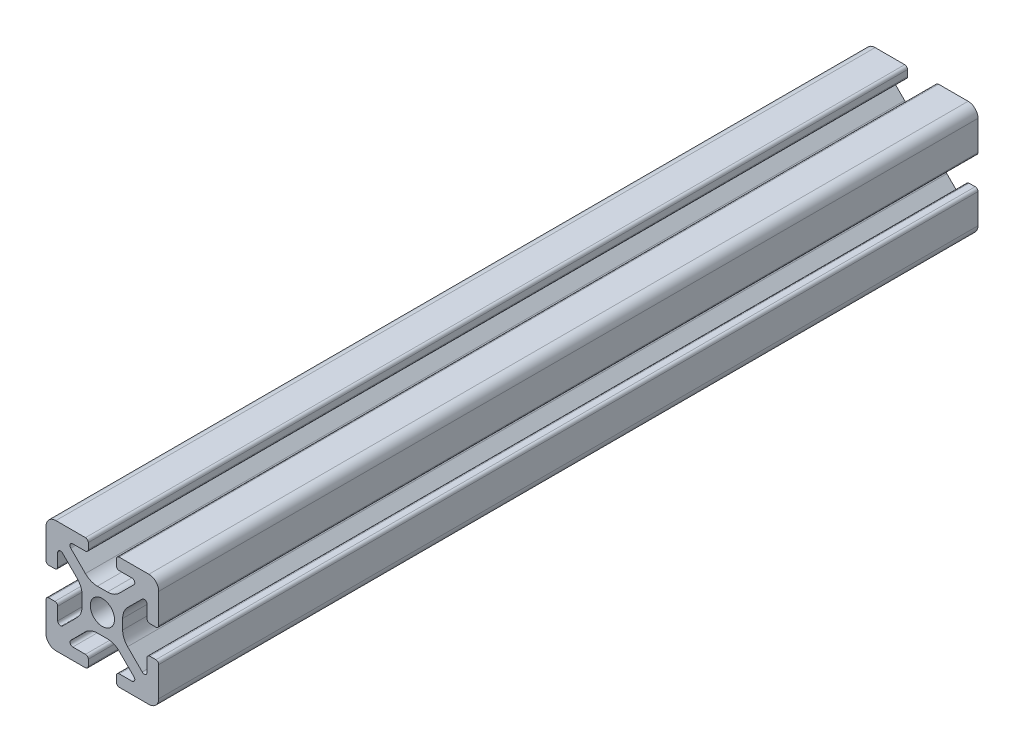
SolidWorks part; units mm, degrees
ref_plane "Front Plane" through (0, 0, 0) normal (0, 0, 1) x (1, 0, 0)
ref_plane "Top Plane" through (0, 0, 0) normal (0, 1, 0) x (1, 0, 0)
ref_plane "Right Plane" through (0, 0, 0) normal (1, 0, 0) x (0, 0, -1)
sketch "Sketch2" plane through (0, 0, 0) normal (0, 0, 1) x (1, 0, 0)
  line L0 (0, 10) -> (0, -10) construction
  line L1 (-10, 0) -> (10, 0) construction
  line L2 (2.5, -10) -> (10, -10)
  line L3 (10, -10) -> (10, -2.5)
  line L4 (2.5, -10) -> (2.5, -7.9246)
  line L5 (2.5, -7.9246) -> (6.4571, -7.9246)
  line L6 (6.4571, -7.9246) -> (2.1325, -3.6)
  line L7 (0, 0) -> (10, -10) construction
  line L8 (10, -2.5) -> (7.9246, -2.5)
  line L9 (7.9246, -2.5) -> (7.9246, -6.4571)
  line L10 (7.9246, -6.4571) -> (3.6, -2.1325)
  line L11 (5.7623, -4.2948) -> (4.2948, -5.7623) construction
  circle A0 centre (0, 0) radius 2.15
  arc A1 (5.25, -7.9246) -> (5.6036, -7.0711) centre (5.25, -7.4246) ccw construction
  point P8 (0, -3.6)
  point P16 (5.0286, -5.0286)
  dimension "Center Hole Diameter" = 4.3
  dimension "D3" = 0.5
  dimension "Rail Height" = 20
  dimension "Rail Width" = 20
  dimension "T-Slot Width" = 5
  dimension "Slot Depth" = 6.4
  dimension "Slot Inner Width" = 11.5
sketch "Sketch3" plane through (0, 0, 0) normal (1, 0, 0) x (0, 0, -1)
  line L0 (-457.2, -10) -> (457.2, -10) construction
  line L1 (-431.8, 0) -> (431.8, 0) construction
  line L2 (0, 10) -> (0, -10) construction
  line L3 (0, 10) -> (0, -10) construction
  point P6 (-431.8, 0)
  point P8 (431.8, 0)
  dimension "Length" = 914.4
  dimension "D1" = 25.4
sketch "Sketch4" plane through (0, 0, 0) normal (0, 0, 1) x (1, 0, 0)
  line L0 (3, -10) -> (8.25, -10)
  line L1 (2.5, -10) -> (10, -10) construction
  line L2 (2.5, -10) -> (2.5, -7.9246) construction
  line L3 (2.5, -7.9246) -> (6.4571, -7.9246) construction
  line L4 (2.5, -8.4246) -> (2.5, -9.5)
  line L5 (3, -7.9246) -> (5.25, -7.9246)
  line L6 (0, -3.6) -> (0.8898, -3.6)
  line L7 (6.4571, -7.9246) -> (2.1325, -3.6) construction
  line L8 (3.0112, -4.4787) -> (5.6036, -7.0711)
  line L9 (10, -10) -> (10, -2.5) construction
  line L10 (7.9246, -6.4571) -> (3.6, -2.1325) construction
  line L11 (7.9246, -2.5) -> (7.9246, -6.4571) construction
  line L12 (7.9246, -5.25) -> (7.9246, -3)
  line L13 (10, -2.5) -> (7.9246, -2.5) construction
  line L14 (8.4246, -2.5) -> (9.5, -2.5)
  line L15 (10, -3) -> (10, -8.25)
  line L16 (7.0711, -5.6036) -> (4.4787, -3.0112)
  line L17 (3.6, 0) -> (3.6, -0.8898)
  line L18 (-10, 0) -> (10, 0) construction
  line L19 (0, -3.6) -> (0, -2.15)
  line L20 (0, 10) -> (0, -10) construction
  line L21 (3.6, 0) -> (2.15, 0)
  arc A0 (2.5, -9.5) -> (3, -10) centre (3, -9.5) ccw
  arc A1 (5.25, -7.9246) -> (5.6036, -7.0711) centre (5.25, -7.4246) ccw construction
  arc A2 (2.5, -8.4246) -> (3, -7.9246) centre (3, -8.4246) cw
  arc A3 (5.25, -7.9246) -> (5.6036, -7.0711) centre (5.25, -7.4246) ccw
  arc A4 (0.8898, -3.6) -> (3.0112, -4.4787) centre (0.8898, -6.6) cw
  arc A5 (8.25, -10) -> (10, -8.25) centre (8.25, -8.25) ccw
  arc A6 (7.0711, -5.6036) -> (7.9246, -5.25) centre (7.4246, -5.25) ccw
  arc A7 (7.9246, -3) -> (8.4246, -2.5) centre (8.4246, -3) cw
  arc A8 (9.5, -2.5) -> (10, -3) centre (9.5, -3) cw
  arc A9 (4.4787, -3.0112) -> (3.6, -0.8898) centre (6.6, -0.8898) cw
  circle A10 centre (0, 0) radius 2.15 construction
  arc A11 (0, -2.15) -> (2.15, 0) centre (0, 0) ccw
  dimension "D1" = 1.75
  dimension "D2" = 3
extrude "Boss-Extrude1" add sketch "Sketch4" along normal mid plane 109
mirror "Mirror1" about plane through (0, 0, 0) normal (1, 0, 0) of bodies 134
mirror "Mirror2" about plane through (0, 0, 0) normal (0, 1, 0) of bodies 135
scale "Scale1" bodies to scale 136 scale about centroid uniform scaling no x scale factor 0.75 y scale factor 0.75 z scale factor 1
equation "\"D3@Sketch2\"=\"T-Slot Width@Sketch2\"*0.1"
equation "\"D1@Sketch4\"=\"D3@Sketch2\"*3.5"
equation "\"D2@Sketch4\"=\"D3@Sketch2\"*6"
equation "\"D1@Boss-Extrude1\"=\"Length@Sketch3\""
